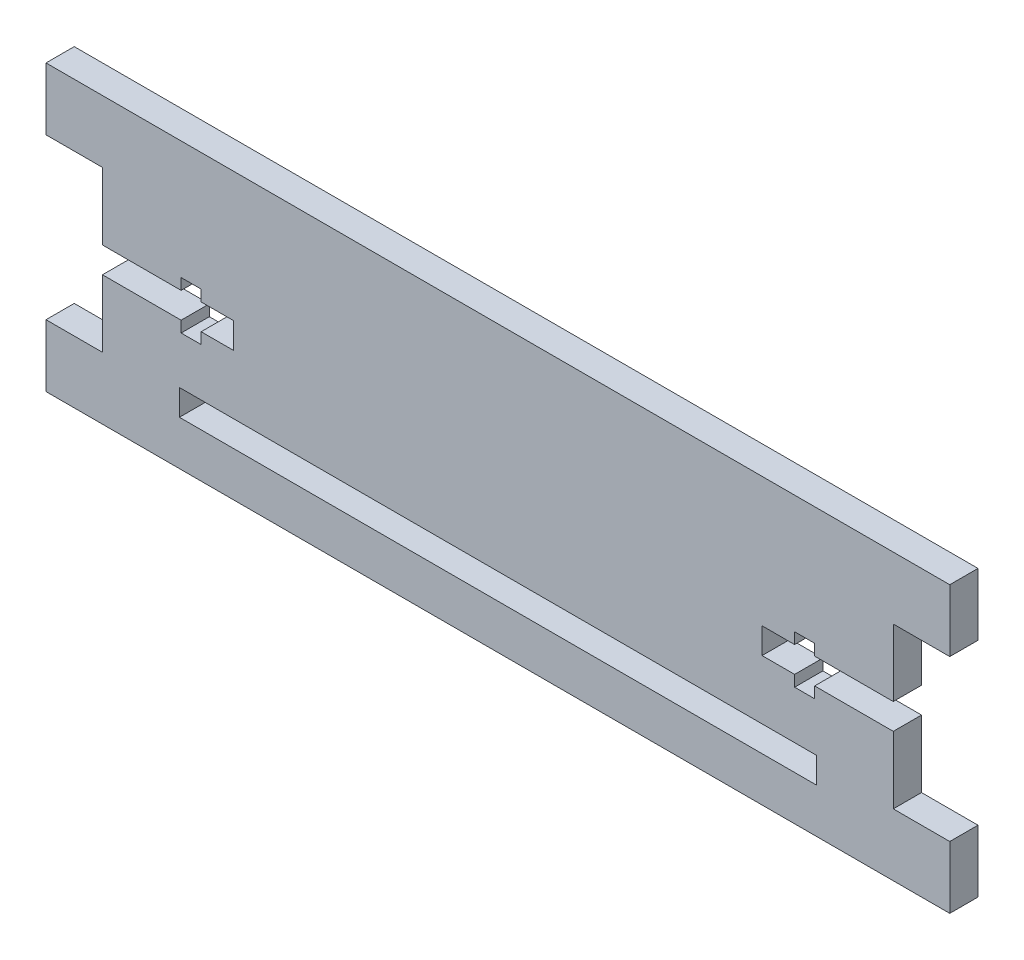
SolidWorks part; units mm, degrees
ref_plane "Front Plane" through (0, 0, 0) normal (0, 0, 1) x (1, 0, 0)
ref_plane "Top Plane" through (0, 0, 0) normal (0, 1, 0) x (1, 0, 0)
ref_plane "Right Plane" through (0, 0, 0) normal (1, 0, 0) x (0, 0, -1)
sketch "Sketch1" plane through (0, 0, 0) normal (0, 0, 1) x (1, 0, 0)
  line L0 (90.4271, 6.036) -> (90.4271, 13.036)
  line L1 (-11.1729, 38.036) -> (90.4271, 38.036)
  line L2 (90.4271, 38.036) -> (90.4271, 31.036)
  line L3 (-11.1729, 6.036) -> (90.4271, 6.036)
  line L4 (-11.1729, 38.036) -> (-11.1729, 31.036)
  line L5 (3.8271, 13.936) -> (75.4271, 13.936)
  line L6 (3.8271, 13.936) -> (3.8271, 11.036)
  line L7 (3.8271, 11.036) -> (75.4271, 11.036)
  line L8 (75.4271, 13.936) -> (75.4271, 11.036)
  line L9 (84.0771, 31.036) -> (90.4271, 31.036)
  line L10 (84.0771, 31.036) -> (84.0771, 23.486)
  line L11 (84.0771, 13.036) -> (90.4271, 13.036)
  line L12 (84.0771, 13.036) -> (84.0771, 20.586)
  line L13 (69.3271, 23.486) -> (72.9871, 23.486)
  line L14 (69.3271, 23.486) -> (69.3271, 20.586)
  line L15 (69.3271, 20.586) -> (72.9871, 20.586)
  line L16 (75.2371, 23.486) -> (84.0771, 23.486)
  line L17 (72.9871, 24.736) -> (75.2371, 24.736)
  line L18 (72.9871, 24.736) -> (72.9871, 23.486)
  line L19 (72.9871, 19.336) -> (75.2371, 19.336)
  line L20 (75.2371, 24.736) -> (75.2371, 23.486)
  line L21 (75.2371, 20.586) -> (84.0771, 20.586)
  line L22 (75.2371, 19.336) -> (75.2371, 20.586)
  line L23 (72.9871, 19.336) -> (72.9871, 20.586)
  line L24 (39.6271, 38.036) -> (39.6271, 6.036) construction
  line L25 (6.2671, 19.336) -> (6.2671, 20.586)
  line L26 (4.0171, 19.336) -> (4.0171, 20.586)
  line L27 (-4.8229, 20.586) -> (4.0171, 20.586)
  line L28 (4.0171, 24.736) -> (4.0171, 23.486)
  line L29 (4.0171, 19.336) -> (6.2671, 19.336)
  line L30 (6.2671, 24.736) -> (6.2671, 23.486)
  line L31 (4.0171, 24.736) -> (6.2671, 24.736)
  line L32 (-4.8229, 23.486) -> (4.0171, 23.486)
  line L33 (6.2671, 20.586) -> (9.9271, 20.586)
  line L34 (9.9271, 23.486) -> (9.9271, 20.586)
  line L35 (6.2671, 23.486) -> (9.9271, 23.486)
  line L36 (-4.8229, 13.036) -> (-4.8229, 20.586)
  line L37 (-11.1729, 13.036) -> (-4.8229, 13.036)
  line L38 (-4.8229, 31.036) -> (-4.8229, 23.486)
  line L39 (-11.1729, 31.036) -> (-4.8229, 31.036)
  line L41 (-11.1729, 6.036) -> (-11.1729, 13.036)
  dimension "D1" = 2.9
  dimension "D2" = 5
  dimension "D3" = 2.9
  dimension "D4" = 2.25
  dimension "D5" = 8.84
  dimension "D6" = 1.25
  dimension "D7" = 1.25
  dimension "D8" = 3.66
  dimension "D9" = 6.35
  dimension "D10" = 15
  dimension "D11" = 7
  dimension "D12" = 101.6
  dimension "D13" = 101.6
  dimension "D14" = 7
  dimension "D15" = 32
  dimension "D16" = 14.55
  dimension "D17" = 15
extrude "Extrude1" add sketch "Sketch1" along normal blind 3.175
